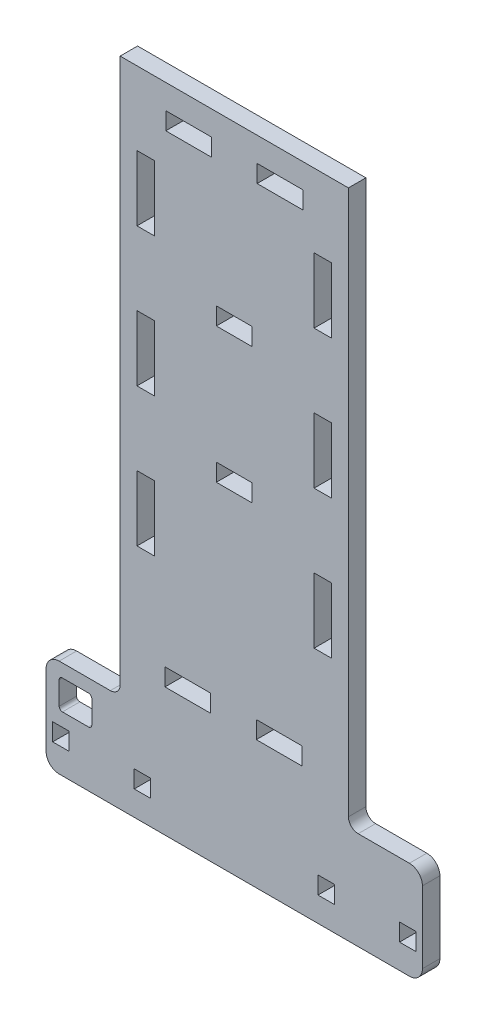
SolidWorks part; units mm, degrees
ref_plane "Front Plane" through (0, 0, 0) normal (0, 0, 1) x (1, 0, 0)
ref_plane "Top Plane" through (0, 0, 0) normal (0, 1, 0) x (1, 0, 0)
ref_plane "Right Plane" through (0, 0, 0) normal (1, 0, 0) x (0, 0, -1)
sketch "Model" plane through (0, 0, 0) normal (0, 0, 1) x (1, 0, 0)
  line L304 (82.1741, 92.5) -> (87.5241, 92.5)
  line L305 (82.1741, 72.5) -> (82.1741, 92.5)
  line L306 (87.5241, 72.5) -> (82.1741, 72.5)
  line L307 (87.5241, 92.5) -> (87.5241, 72.5)
  line L308 (27.8641, 92.5) -> (33.2141, 92.5)
  line L309 (27.8641, 72.5) -> (27.8641, 92.5)
  line L310 (33.2141, 72.5) -> (27.8641, 72.5)
  line L311 (33.2141, 92.5) -> (33.2141, 72.5)
  line L312 (63.1941, 106.925) -> (63.1941, 101.575)
  line L313 (52.1941, 106.925) -> (63.1941, 106.925)
  line L314 (52.1941, 101.575) -> (52.1941, 106.925)
  line L315 (63.1941, 101.575) -> (52.1941, 101.575)
  line L316 (82.1741, 135) -> (87.5241, 135)
  line L317 (82.1741, 115) -> (82.1741, 135)
  line L318 (87.5241, 115) -> (82.1741, 115)
  line L319 (87.5241, 135) -> (87.5241, 115)
  line L320 (27.8641, 135) -> (33.2141, 135)
  line L321 (27.8641, 115) -> (27.8641, 135)
  line L322 (33.2141, 115) -> (27.8641, 115)
  line L323 (33.2141, 135) -> (33.2141, 115)
  line L324 (27.8641, 177.5) -> (33.2141, 177.5)
  line L325 (27.8641, 157.5) -> (27.8641, 177.5)
  line L326 (33.2141, 157.5) -> (27.8641, 157.5)
  line L327 (33.2141, 177.5) -> (33.2141, 157.5)
  line L328 (82.1741, 177.5) -> (87.5241, 177.5)
  line L329 (82.1741, 157.5) -> (82.1741, 177.5)
  line L330 (87.5241, 157.5) -> (82.1741, 157.5)
  line L331 (87.5241, 177.5) -> (87.5241, 157.5)
  line L332 (63.1941, 148.425) -> (63.1941, 143.075)
  line L333 (52.1941, 148.425) -> (63.1941, 148.425)
  line L334 (52.1941, 143.075) -> (52.1941, 148.425)
  line L335 (63.1941, 143.075) -> (52.1941, 143.075)
  line L336 (50.6941, 187.15) -> (50.6941, 192.5)
  line L337 (50.6941, 192.5) -> (36.6941, 192.5)
  line L338 (36.6941, 192.5) -> (36.6941, 187.15)
  line L339 (36.6941, 187.15) -> (50.6941, 187.15)
  line L340 (78.6941, 187.15) -> (78.6941, 192.5)
  line L341 (78.6941, 192.5) -> (64.6941, 192.5)
  line L342 (64.6941, 192.5) -> (64.6941, 187.15)
  line L343 (64.6941, 187.15) -> (78.6941, 187.15)
  line L344 (78.4441, 44.7) -> (64.4441, 44.7)
  line L345 (64.4441, 44.7) -> (64.4441, 39.35)
  line L346 (64.4441, 39.35) -> (78.4441, 39.35)
  line L347 (50.4441, 39.35) -> (50.4441, 44.7)
  line L348 (50.4441, 44.7) -> (36.4441, 44.7)
  line L349 (36.4441, 44.7) -> (36.4441, 39.35)
  line L350 (36.4441, 39.35) -> (50.4441, 39.35)
  line L351 (88.3691, 7.55) -> (88.3691, 12.9)
  line L352 (88.3691, 12.9) -> (83.3691, 12.9)
  line L353 (83.3691, 12.9) -> (83.3691, 7.55)
  line L354 (83.3691, 7.55) -> (88.3691, 7.55)
  line L355 (113.3691, 7.55) -> (113.3691, 12.9)
  line L356 (113.3691, 12.9) -> (108.3691, 12.9)
  line L357 (108.3691, 12.9) -> (108.3691, 7.55)
  line L358 (108.3691, 7.55) -> (113.3691, 7.55)
  line L359 (2.0191, 12.9) -> (2.0191, 7.55)
  line L360 (2.0191, 7.55) -> (7.0191, 7.55)
  line L361 (7.0191, 7.55) -> (7.0191, 12.9)
  line L362 (7.0191, 12.9) -> (2.0191, 12.9)
  line L363 (27.0191, 12.9) -> (27.0191, 7.55)
  line L364 (27.0191, 7.55) -> (32.0191, 7.55)
  line L365 (32.0191, 7.55) -> (32.0191, 12.9)
  line L366 (32.0191, 12.9) -> (27.0191, 12.9)
  line L367 (13, 17) -> (5, 17)
  line L368 (14, 25) -> (14, 18)
  line L369 (5, 26) -> (13, 26)
  line L370 (4, 18) -> (4, 25)
  line L371 (78.4441, 39.35) -> (78.4441, 44.7)
  line L372 (4, 30) -> (19.6941, 30)
  line L373 (0, 4) -> (0, 26)
  line L374 (111.3883, 0) -> (4, 0)
  line L375 (115.3883, 26) -> (115.3883, 4)
  line L376 (95.6941, 30) -> (111.3883, 30)
  line L377 (92.6941, 200) -> (92.6941, 33)
  line L378 (22.6941, 200) -> (92.6941, 200)
  line L379 (22.6941, 33) -> (22.6941, 200)
  arc A30 (4, 30) -> (0, 26) centre (4, 26) ccw
  arc A31 (19.6941, 30) -> (22.6941, 33) centre (19.6941, 33) ccw
  arc A32 (92.6941, 33) -> (95.6941, 30) centre (95.6941, 33) ccw
  arc A33 (115.3883, 26) -> (111.3883, 30) centre (111.3883, 26) ccw
  arc A34 (111.3883, 0) -> (115.3883, 4) centre (111.3883, 4) ccw
  arc A35 (0, 4) -> (4, 0) centre (4, 4) ccw
  arc A36 (4, 18) -> (5, 17) centre (5, 18) ccw
  arc A37 (13, 17) -> (14, 18) centre (13, 18) ccw
  arc A38 (14, 25) -> (13, 26) centre (13, 25) ccw
  arc A39 (5, 26) -> (4, 25) centre (5, 25) ccw
extrude "Boss-Extrude1" add sketch "Model" along normal blind 5.35
